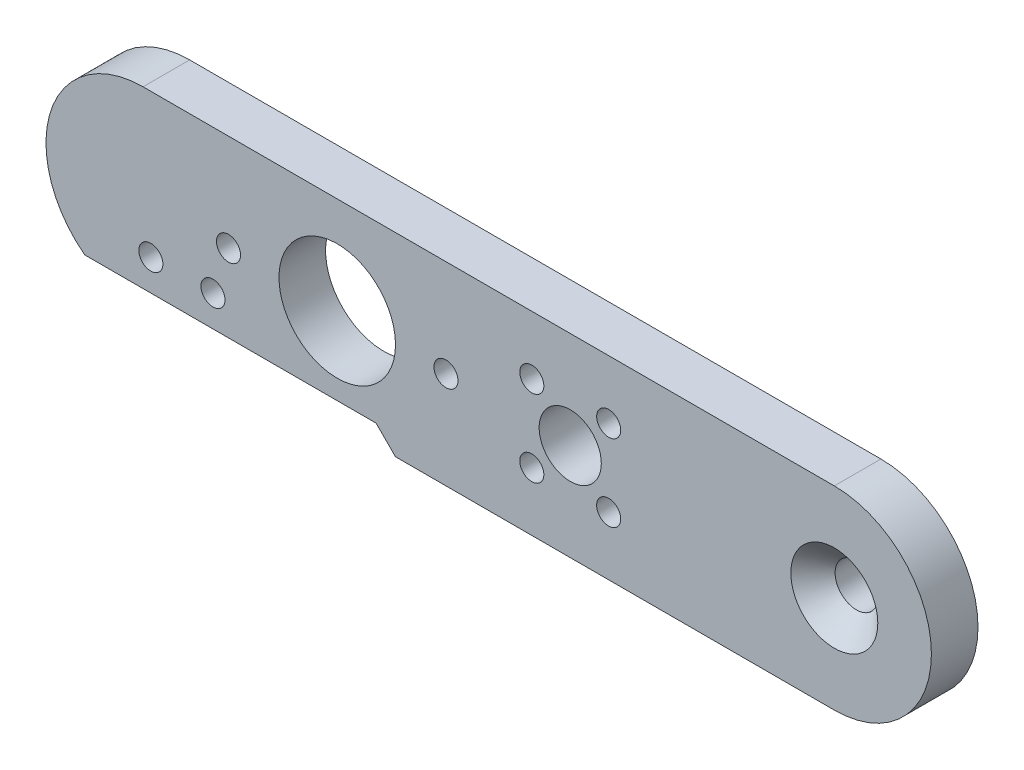
SolidWorks part; units mm, degrees
ref_plane "Front Plane" through (0, 0, 0) normal (0, 0, 1) x (1, 0, 0)
ref_plane "Top Plane" through (0, 0, 0) normal (0, 1, 0) x (1, 0, 0)
ref_plane "Right Plane" through (0, 0, 0) normal (1, 0, 0) x (0, 0, -1)
sketch "Sketch2" plane through (0, 0, 0) normal (0, 0, 1) x (1, 0, 0)
  line L0 (-44.5692, 0) -> (44.4308, 0) construction
  line L1 (-44.5692, 12.5) -> (44.4308, 12.5)
  line L2 (-12.0692, -12.5) -> (44.4308, -12.5)
  line L3 (10.4308, 0) -> (15.3805, 4.9497) construction
  line L4 (10.4308, 0) -> (10.4308, 7) construction
  line L5 (-52.0692, -10) -> (-14.5692, -10)
  line L6 (-14.5692, -10) -> (-12.0692, -12.5)
  arc A0 (-44.5692, 12.5) -> (-52.0692, -10) centre (-44.5692, 0) ccw
  arc A1 (44.4308, -12.5) -> (44.4308, 12.5) centre (44.4308, 0) ccw
  circle A2 centre (10.4308, 0) radius 4
  circle A3 centre (10.4308, 0) radius 7 construction
  circle A4 centre (15.3805, 4.9497) radius 1.55
  circle A5 centre (15.3805, -4.9497) radius 1.55
  circle A6 centre (5.481, -4.9497) radius 1.55
  circle A7 centre (5.481, 4.9497) radius 1.55
  circle A8 centre (-19.5692, 0) radius 7.5
  circle A9 centre (-5.5692, 0) radius 1.55
  circle A10 centre (-33.5692, 0) radius 1.55
  point P3 (-0.0692, 0)
  point P23 (10.4308, 0)
  dimension "D2" = 12.5
  dimension "D3" = 8
  dimension "D5" = 14
  dimension "D6" = 45
  dimension "D7" = 3.1
  dimension "D12" = 15
  dimension "D13" = 3.1
  dimension "D14" = 3.1
  dimension "D1" = 89
  dimension "D4" = 34
  dimension "D9" = 45
  dimension "D10" = 59
  dimension "D11" = 22.5
  dimension "D15" = 30
  dimension "D16" = 14
  dimension "D17" = 14
  dimension "D8" = 4
extrude "Boss-Extrude1" add sketch "Sketch2" along normal blind 6
hole_wizard "CSK for M5 SFHCS1" positions "3DSketch1" profile "Sketch4" countersink size "M5" standard "ANSI Metric" end condition through all
sketch3d "3DSketch1"
  line L0 (44.4308, 0, 6) -> (44.4308, 0, 0) construction
  point P0 (44.4308, 0, 6)
sketch "Sketch4" plane through (44.4308, 0, 6) normal (1, 0, 0) x (0, -1, 0)
  line L0 (0, 0) -> (0, 6)
  line L1 (0, 6) -> (2.75, 6)
  line L2 (2.75, 6) -> (2.75, 2.85)
  line L3 (2.75, 2.85) -> (5.6, 0)
  line L5 (5.6, 0) -> (0, 0)
  line L6 (-2.75, 2.85) -> (-5.6, 0) construction
  line L11 (0, -6.35) -> (0, 107.95) construction
  dimension "Thru Hole Dia." = 5.5
  dimension "Thru Hole Depth" = 6
  dimension "Near C'Sink Dia." = 11.2
  dimension "Near C'Sink Angle" = 90
sketch "Sketch6" plane through (0, 0, 6) normal (0, 0, 1) x (1, 0, 0)
  line L0 (-51.543, -6) -> (-26.9813, -6) construction
  line L1 (44.4308, 12.5) -> (-44.5692, 12.5) construction
  line L2 (-12.1575, 1.1473) -> (-19.5692, 0) construction
  line L3 (-19.5692, 0) -> (-19.5692, -6) construction
  line L4 (-19.5692, -6) -> (-35.5692, -6) construction
  circle A0 centre (-35.5692, -6) radius 1.55
  circle A1 centre (-43.5692, -6) radius 1.55
  circle A2 centre (-19.5692, 0) radius 7.5 construction
  dimension "D2" = 3.1
  dimension "D3" = 3.1
  dimension "D1" = 18.5
  dimension "D4" = 16
  dimension "D5" = 8
extrude "Cut-Extrude1" cut sketch "Sketch6" against normal blind 3
sketch "Sketch7" plane through (0, 0, 3) normal (0, 0, 1) x (1, 0, 0)
  circle A0 centre (-35.5692, -6) radius 3
  circle A1 centre (-43.5692, -6) radius 3
  dimension "D1" = 6
  dimension "D2" = 6
extrude "Cut-Extrude2" cut sketch "Sketch7" against normal through all
